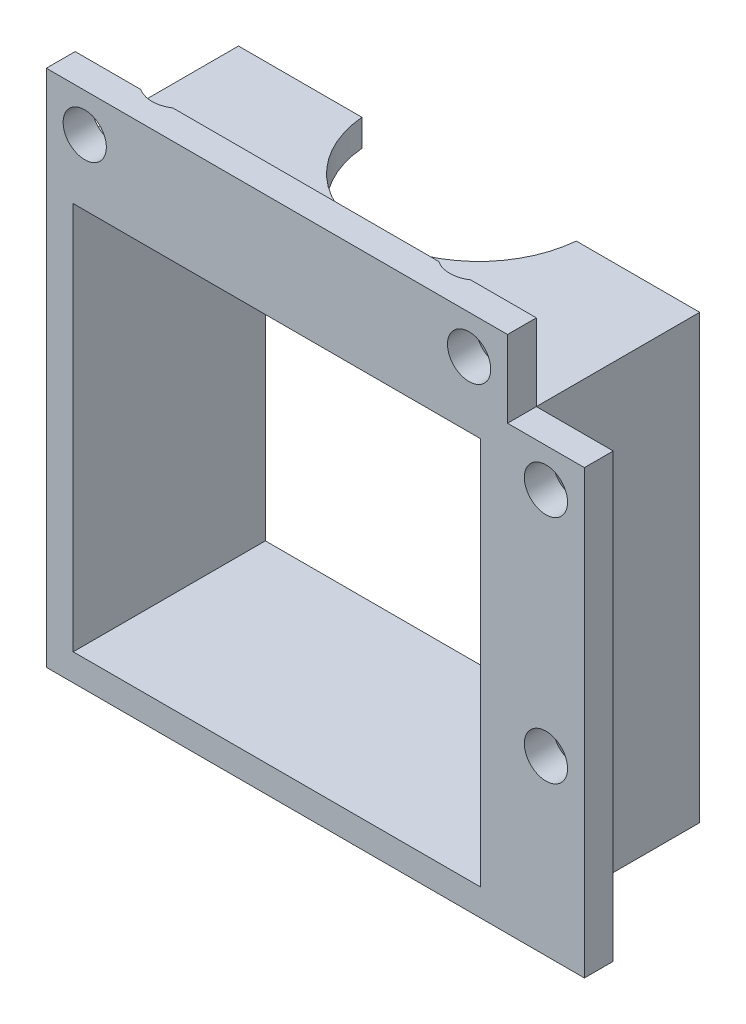
SolidWorks part; units mm, degrees
material "ABS"
ref_plane "前视基准面" through (0, 0, 0) normal (0, 0, 1) x (1, 0, 0)
ref_plane "上视基准面" through (0, 0, 0) normal (0, 1, 0) x (1, 0, 0)
ref_plane "右视基准面" through (0, 0, 0) normal (1, 0, 0) x (0, 0, -1)
sketch "Sketch1" plane through (0, 0, 0) normal (0, 0, 1) x (1, 0, 0)
  line L0 (-28.1067, -26.5) -> (19.8933, -26.5)
  line L5 (19.8933, -26.5) -> (19.8933, -72.5)
  line L6 (-28.1067, -72.5) -> (19.8933, -72.5)
  line L7 (-28.1067, -26.5) -> (-28.1067, -72.5)
  line L8 (-25.3067, -29.3) -> (17.0933, -29.3)
  line L9 (17.0933, -29.3) -> (17.0933, -69.7)
  line L10 (-25.3067, -69.7) -> (17.0933, -69.7)
  line L11 (-25.3067, -29.3) -> (-25.3067, -69.7)
extrude "Boss-Extrude1" add sketch "Sketch1" against normal blind 20
sketch "Sketch3" plane through (0, -26.5, 0) normal (0, 1, 0) x (1, 0, 0)
  circle A0 centre (-4.1067, 21) radius 11.2
  dimension "D1" = 22.4
extrude "Cut-Extrude1" cut sketch "Sketch3" against normal up to next
sketch "Sketch5" plane through (0, -26.5, 0) normal (0, 1, 0) x (1, 0, 0)
  circle A8 centre (11.3933, 5.5) radius 1.7
  circle A9 centre (-19.6067, 5.5) radius 1.7
  dimension "D1" = 3.4
extrude "Cut-Extrude2" cut sketch "Sketch5" against normal up to next
sketch "Sketch6" plane through (0, 0, 0) normal (0, 0, 1) x (1, 0, 0)
  line L5 (19.8933, -26.5) -> (-28.1067, -26.5) construction
  line L6 (19.8933, -72.5) -> (19.8933, -26.5) construction
  line L11 (-28.1067, -26.5) -> (-28.1067, -72.5) construction
  line B0 (27.8933, -72.5) -> (27.8933, -26.5)
  line B1 (27.8933, -72.5) -> (19.8933, -72.5)
  line B2 (19.8933, -72.5) -> (19.8933, -26.5)
  line B3 (27.8933, -26.5) -> (19.8933, -26.5)
  line B4 (19.8933, -49.5) -> (27.8933, -49.5) construction
  line B5 (23.8933, -72.5) -> (23.8933, -26.5) construction
  circle B6 centre (23.8933, -54.5) radius 2.25
  circle B7 centre (23.8933, -30.5) radius 2.25
  line B8 (19.8933, -18.5) -> (-28.1067, -18.5)
  line B9 (19.8933, -18.5) -> (19.8933, -26.5)
  line B10 (19.8933, -26.5) -> (-28.1067, -26.5)
  line B11 (-28.1067, -18.5) -> (-28.1067, -26.5)
  line B12 (-4.1067, -26.5) -> (-4.1067, -18.5) construction
  line B13 (19.8933, -22.5) -> (-28.1067, -22.5) construction
  circle B14 centre (15.8933, -22.5) radius 2.25
  circle B15 centre (-24.1067, -22.5) radius 2.25
sketch_block_instance "Block1-3"
sketch_block "Block1" parameters "D3"=4.5, "D1"=8, "D2"=22, "D4"=5, "D5"=19
sketch_block_instance "Block2-1"
sketch_block "Block2" parameters "D2"=4.5, "D1"=8, "D3"=20, "D4"=20, "D5"=48
extrude "Boss-Extrude2" add sketch "Sketch6" against normal blind 3
sketch "Sketch7" plane through (0, -18.5, 0) normal (0, 1, 0) x (1, 0, 0)
  circle A0 centre (11.3933, 5.5) radius 3
  circle A1 centre (-19.6067, 5.5) radius 3
  dimension "D1" = 6
extrude "Cut-Extrude3" cut sketch "Sketch7" against normal up to surface (8 mm away) up to face at (-4.1067, -26.5, -12.6333)
